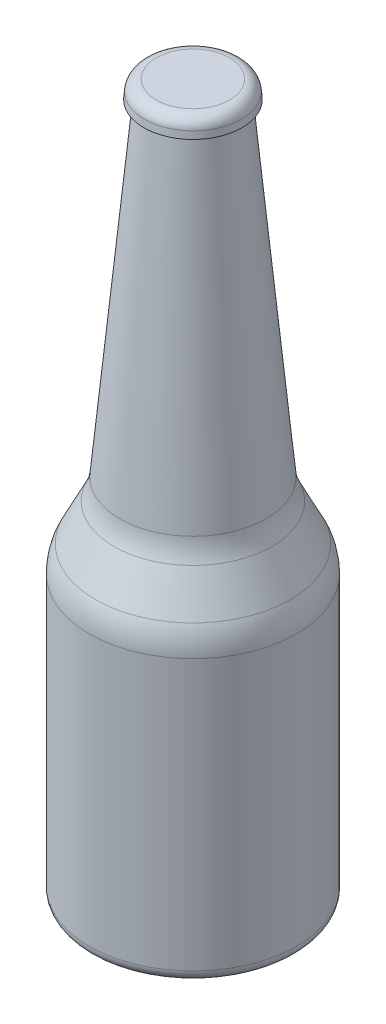
SolidWorks part; units mm, degrees
ref_plane "Front Plane" through (0, 0, 0) normal (0, 0, 1) x (1, 0, 0)
ref_plane "Top Plane" through (0, 0, 0) normal (0, 1, 0) x (1, 0, 0)
ref_plane "Right Plane" through (0, 0, 0) normal (1, 0, 0) x (0, 0, -1)
sketch "Sketch1" plane through (0, 0, 0) normal (0, 0, 1) x (1, 0, 0)
  line L0 (0, 0) -> (0, 1.0944) construction
  line L1 (0, 0) -> (-0.175, 0)
  line L2 (-0.175, 0) -> (-0.175, 0.5)
  line L3 (-0.175, 0.5) -> (-0.125, 0.6)
  line L4 (-0.125, 0.6) -> (-0.072, 1.169)
  line L6 (0, 1.2) -> (0, 0)
  line L7 (0, 1.2) -> (-0.08, 1.2)
  line L8 (-0.08, 1.2) -> (-0.0828, 1.17)
  line L9 (-0.0828, 1.17) -> (-0.072, 1.169)
  dimension "D1" = 1.2
  dimension "D2" = 0.35
  dimension "D3" = 0.25
  dimension "D4" = 0.5
  dimension "D5" = 0.6
  dimension "D6" = 0.072
  dimension "D7" = 0.08
  dimension "D8" = 0.03
revolve "Revolve1" add sketch "Sketch1" angle 360 about L0
fillet "Fillet1" radius 0.1 2 edges at (0, 0.5, -0.175) (0, 0.6, -0.125)
fillet "Fillet2" radius 0.02 2 edges at (0, 0, -0.175) (0, 1.2, -0.08)
